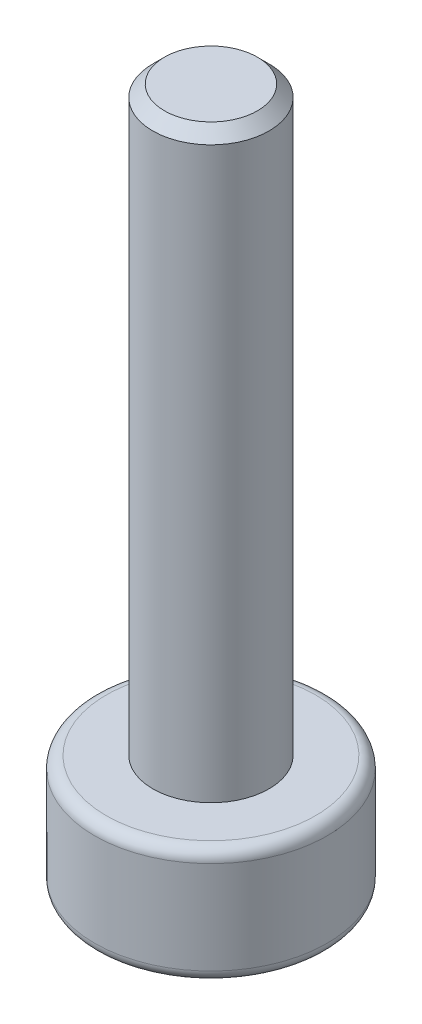
SolidWorks part; units mm, degrees
material "AISI 304"
ref_plane "前视基准面" through (0, 0, 0) normal (0, 0, 1) x (1, 0, 0)
ref_plane "上视基准面" through (0, 0, 0) normal (0, 1, 0) x (1, 0, 0)
ref_plane "右视基准面" through (0, 0, 0) normal (1, 0, 0) x (0, 0, -1)
sketch "草图2" plane through (0, 0, 0) normal (0, 1, 0) x (1, 0, 0)
  circle A0 centre (0, 0) radius 2
  dimension "D1" = 4
extrude "凸台-拉伸1" add sketch "草图2" along normal blind 2
sketch "草图3" plane through (0, 2, 0) normal (0, 1, 0) x (1, 0, 0)
  circle A0 centre (0, 0) radius 1
  dimension "D1" = 2
extrude "凸台-拉伸2" add sketch "草图3" along normal blind 10
fillet "圆角1" radius 0.2 2 edges at (0, 2, 2) (0, 0, 2)
sketch "草图4" plane through (0, 0, 0) normal (0, -1, 0) x (1, 0, 0)
  circle A0 centre (0, 0) radius 0.765
  dimension "D1" = 1.53
extrude "切除-拉伸1" cut sketch "草图4" against normal blind 1.52
chamfer "倒角1" distance 0.1 angle 45 1 edges at (0, 0, -0.765)
chamfer "倒角2" distance 0.2 angle 45 1 edges at (0, 12, 1)
